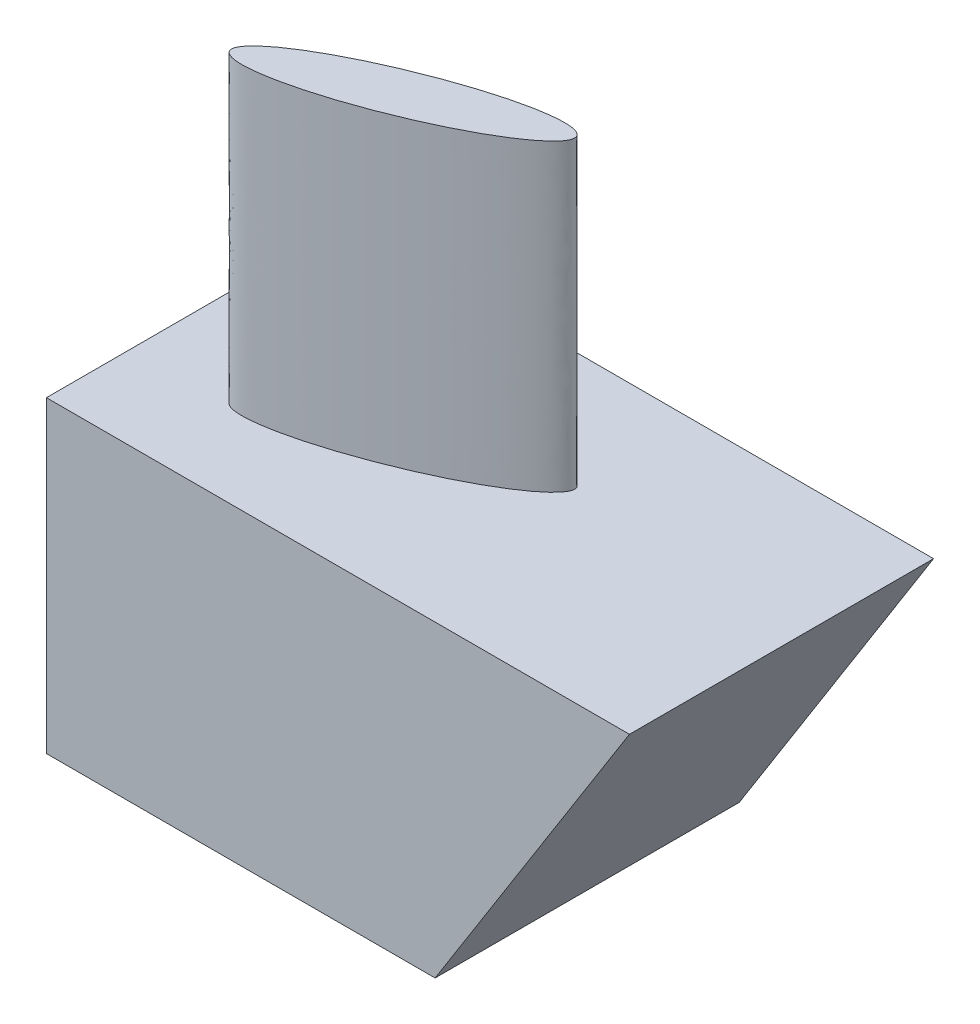
SolidWorks part; units mm, degrees
ref_plane "Front Plane" through (0, 0, 0) normal (0, 0, 1) x (1, 0, 0)
ref_plane "Top Plane" through (0, 0, 0) normal (0, 1, 0) x (1, 0, 0)
ref_plane "Right Plane" through (0, 0, 0) normal (1, 0, 0) x (0, 0, -1)
sketch "Sketch1" plane through (0, 0, 0) normal (0, 0, 1) x (1, 0, 0)
  line L1 (0, 0) -> (101.6, 0)
  line L2 (0, 0) -> (0, 80.5725)
  line L3 (0, 80.5725) -> (152.4, 80.5725)
  line L4 (101.6, 0) -> (152.4, 80.5725)
  point P4 (154.8692, 81.6163)
  point P5 (0, 0)
  point P7 (98.9202, 0)
  point P8 (145.6405, 67.7733)
  point P9 (152.4, 77.611)
  dimension "D1" = 152.4
  dimension "D2" = 95.25
  dimension "D3" = 101.6
extrude "Boss-Extrude1" add sketch "Sketch1" along normal blind 79.502
sketch "Sketch2" plane through (0, 80.5725, 0) normal (0, 1, 0) x (1, 0, 0)
  ellipse E0 centre (57.2689, -43.5267) end of major axis (89.6571, -30.6001) minor radius 7.1368
extrude "Boss-Extrude2" add sketch "Sketch2" along normal blind 79.502
